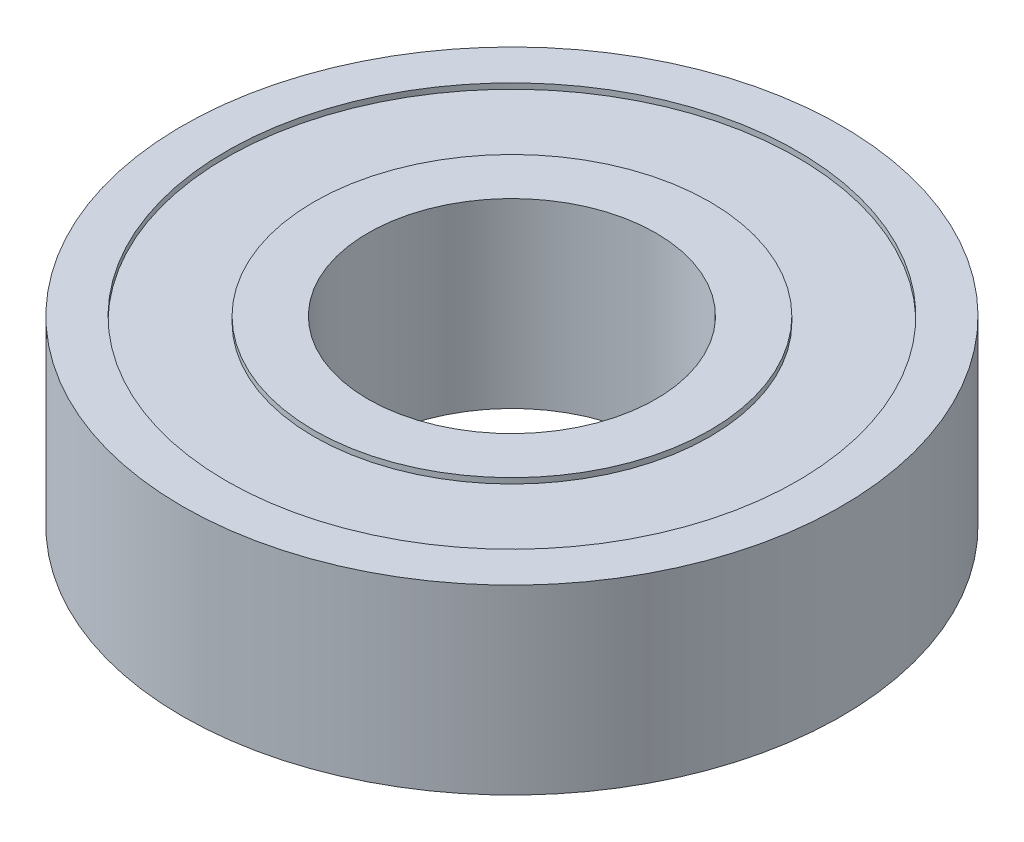
SolidWorks part; units mm, degrees
ref_plane "Plano frontal" through (0, 0, 0) normal (0, 0, 1) x (1, 0, 0)
ref_plane "Plano superior" through (0, 0, 0) normal (0, 1, 0) x (1, 0, 0)
ref_plane "Plano direito" through (0, 0, 0) normal (1, 0, 0) x (0, 0, -1)
sketch "Esboço1" plane through (0, 0, 0) normal (0, 1, 0) x (1, 0, 0)
  circle A0 centre (-2.4895, 0) radius 14.32
extrude "Ressalto-extrusão1" add sketch "Esboço1" along normal blind 7.9
sketch "Esboço2" plane through (0, 7.9, 0) normal (0, 1, 0) x (1, 0, 0)
  circle A0 centre (-2.4895, 0) radius 6.255
  dimension "D1" = 12.51
extrude "Corte-extrusão1" cut sketch "Esboço2" against normal blind 7.9
sketch "Esboço3" plane through (0, 7.9, 0) normal (0, 1, 0) x (1, 0, 0)
  circle A0 centre (-2.4895, 0) radius 12.41
  circle A1 centre (-2.4895, 0) radius 8.6
extrude "Corte-extrusão2" cut sketch "Esboço3" against normal blind 0.24
sketch "Esboço4" plane through (0, 0, 0) normal (1, 0, 0) x (0, 0, -1)
  line L0 (-14.32, 3.95) -> (17.7879, 3.95) construction
  line L1 (-14.32, 7.9) -> (-14.32, 0) construction
ref_plane "Plano1" through (0, 3.95, 0) normal (0, 1, 0) x (1, 0, 0)
mirror "Espelhar1" about plane through (0, 3.95, 0) normal (0, 1, 0) of "Corte-extrusão2"
